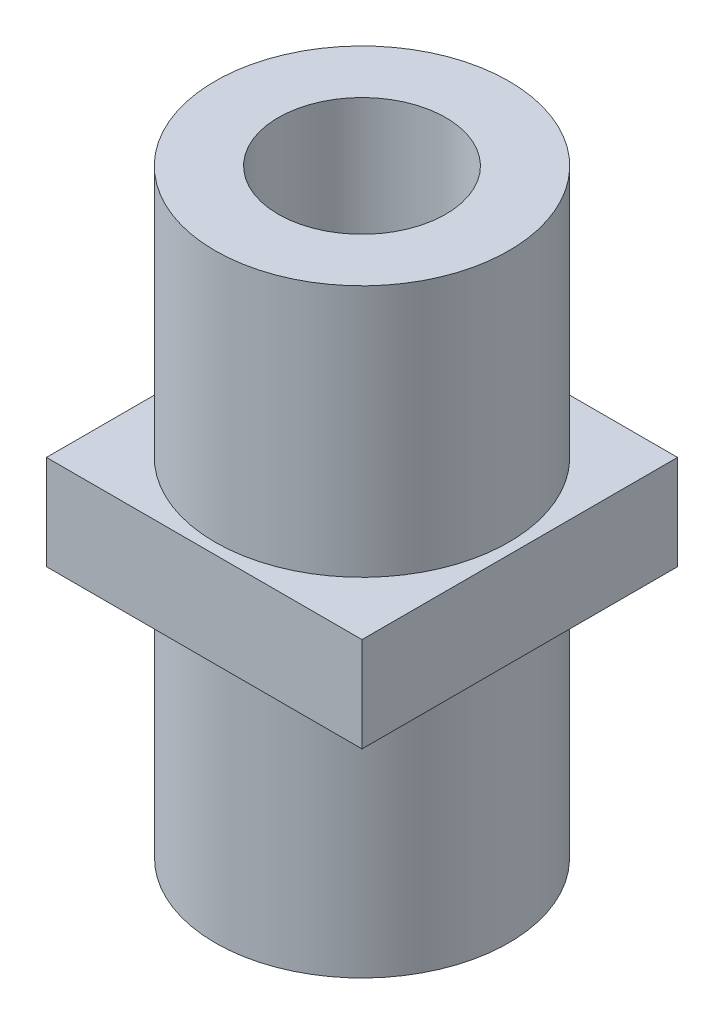
SolidWorks part; units mm, degrees
ref_plane "Front Plane" through (0, 0, 0) normal (0, 0, 1) x (1, 0, 0)
ref_plane "Top Plane" through (0, 0, 0) normal (0, 1, 0) x (1, 0, 0)
ref_plane "Right Plane" through (0, 0, 0) normal (1, 0, 0) x (0, 0, -1)
sketch "Sketch1" plane through (0, 0, 0) normal (0, 1, 0) x (1, 0, 0)
  circle A0 centre (0, 0) radius 4.65
  dimension "D1" = 9.3
extrude "Boss-Extrude1" add sketch "Sketch1" along normal blind 8
sketch "Sketch2" plane through (0, 8, 0) normal (0, 1, 0) x (1, 0, 0)
  line L1 (-5, 5) -> (5, 5)
  line L2 (-5, 5) -> (-5, -5)
  line L3 (-5, -5) -> (5, -5)
  line L4 (5, 5) -> (5, -5)
  line L5 (-5, 5) -> (5, -5) construction
  line L6 (-5, -5) -> (5, 5) construction
  point P0 (0, 0)
  dimension "D1" = 10
  dimension "D2" = 10
extrude "Boss-Extrude2" add sketch "Sketch2" along normal blind 3
sketch "Sketch3" plane through (0, 11, 0) normal (0, 1, 0) x (1, 0, 0)
  circle A0 centre (0, 0) radius 4.655
  dimension "D1" = 9.31
extrude "Boss-Extrude3" add sketch "Sketch3" along normal blind 8
sketch "Sketch4" plane through (0, 19, 0) normal (0, 1, 0) x (1, 0, 0)
  circle A3 centre (0, 0) radius 2.655
  circle A4 centre (0, 0) radius 2.655
  dimension "D1" = 2
extrude "Cut-Extrude1" cut sketch "Sketch4" against normal through all both and the other way through all contours A4
